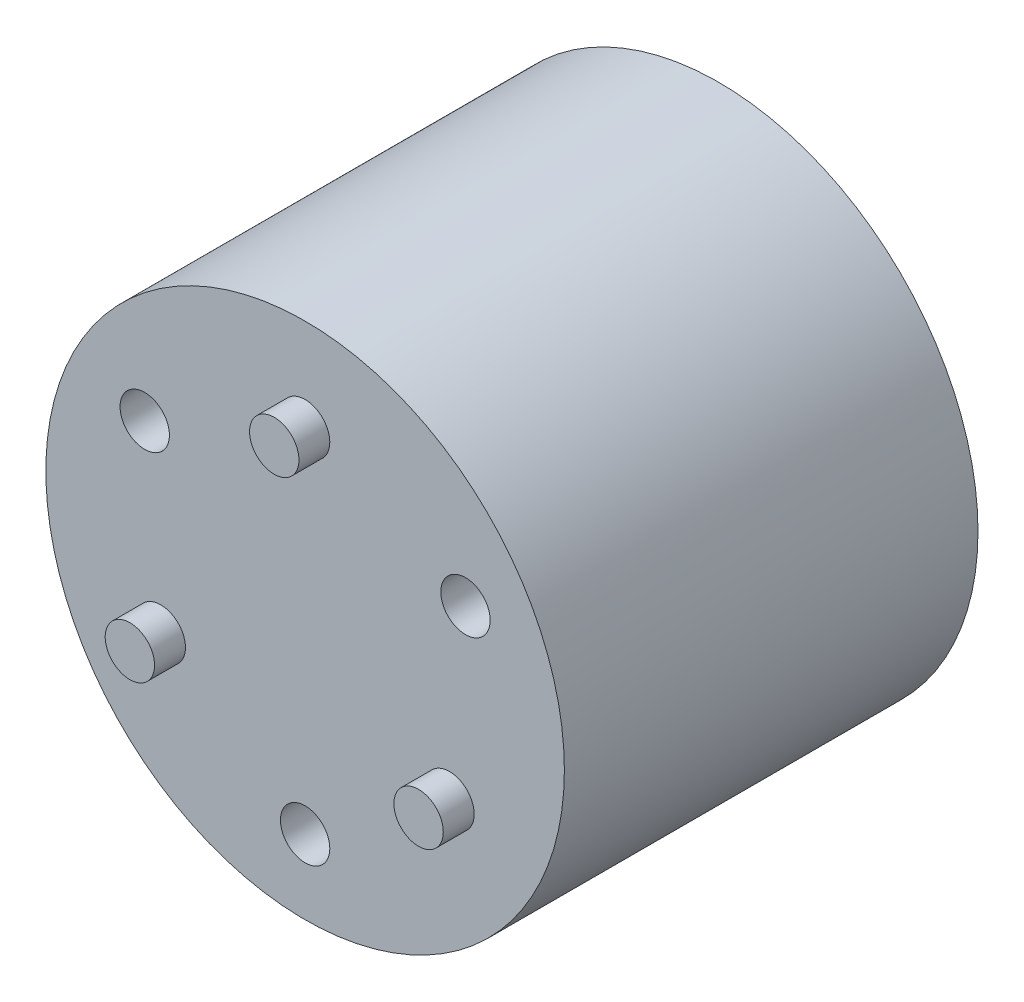
SolidWorks part; units mm, degrees
ref_plane "Front Plane" through (0, 0, 0) normal (0, 0, 1) x (1, 0, 0)
ref_plane "Top Plane" through (0, 0, 0) normal (0, 1, 0) x (1, 0, 0)
ref_plane "Right Plane" through (0, 0, 0) normal (1, 0, 0) x (0, 0, -1)
sketch "Sketch1" plane through (0, 0, 0) normal (1, 0, 0) x (0, 0, -1)
  line L0 (0, 0) -> (31.1882, 0) construction
sketch "Sketch2" plane through (0, 0, 0) normal (0, 0, 1) x (1, 0, 0)
  circle A0 centre (0, 0) radius 21
  point P0 (0, 0)
  dimension "D1" = 42
extrude "Boss-Extrude1" add sketch "Sketch2" against normal blind 33.5
sketch "Sketch3" plane through (0, 0, 0) normal (0, 0, 1) x (1, 0, 0)
  circle A0 centre (0, 0) radius 15 construction
  circle A1 centre (0, -15) radius 2
  circle A2 centre (-12.9904, 7.5) radius 2
  circle A3 centre (12.9904, 7.5) radius 2
  point P3 (0, -15)
  point P12 (0, 0)
  dimension "D1" = 30
  dimension "D2" = 4
  dimension "D3" = 3
extrude "Cut-Extrude2" cut sketch "Sketch3" against normal blind 4
sketch "Sketch4" plane through (0, 0, 0) normal (0, 0, 1) x (1, 0, 0)
  circle A0 centre (0, 0) radius 13.5 construction
  circle A1 centre (0, 13.5) radius 2
  circle A2 centre (11.6913, -6.75) radius 2
  circle A3 centre (-11.6913, -6.75) radius 2
  point P11 (0, 0)
  dimension "D1" = 27
  dimension "D2" = 3
extrude "Boss-Extrude2" add sketch "Sketch4" along normal blind 2.5
